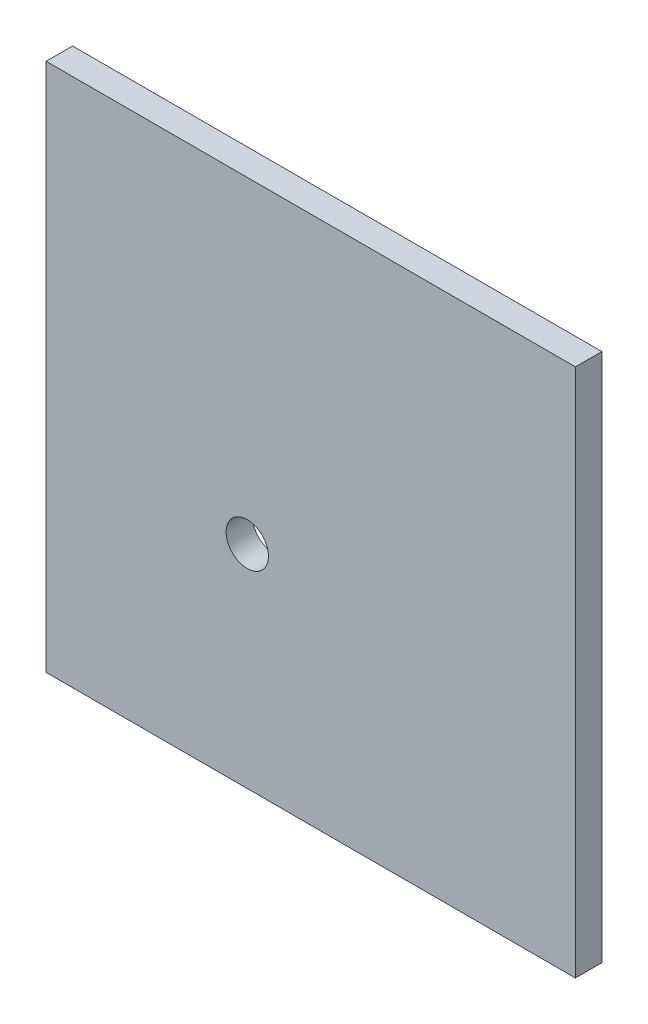
SolidWorks part; units mm, degrees
ref_plane "正面" through (0, 0, 0) normal (0, 0, 1) x (1, 0, 0)
ref_plane "平面" through (0, 0, 0) normal (0, 1, 0) x (1, 0, 0)
ref_plane "右側面" through (0, 0, 0) normal (1, 0, 0) x (0, 0, -1)
sketch "Sketch1" plane through (0, 0, 0) normal (0, 0, 1) x (1, 0, 0)
  line L1 (-50, 50) -> (50, 50)
  line L2 (-50, 50) -> (-50, -50)
  line L3 (-50, -50) -> (50, -50)
  line L4 (50, 50) -> (50, -50)
  line L5 (-50, 50) -> (50, -50) construction
  line L6 (-50, -50) -> (50, 50) construction
  point P0 (0, 0)
  dimension "D1" = 100
  dimension "D2" = 100
extrude "Boss-Extrude1" add sketch "Sketch1" along normal blind 5
sketch "Sketch3" plane through (0, 0, 5) normal (0, 0, 1) x (1, 0, 0)
  line L0 (-50, -10) -> (50, -10) construction
  line L1 (-50, 50) -> (-50, -50) construction
  line L2 (50, -50) -> (50, 50) construction
  line L3 (-50, -50) -> (50, -50) construction
  circle A0 centre (-12, -10) radius 4
  dimension "D3" = 8
  dimension "D1" = 40
  dimension "D2" = 38
extrude "Cut-Extrude1" cut sketch "Sketch3" against normal up to next
